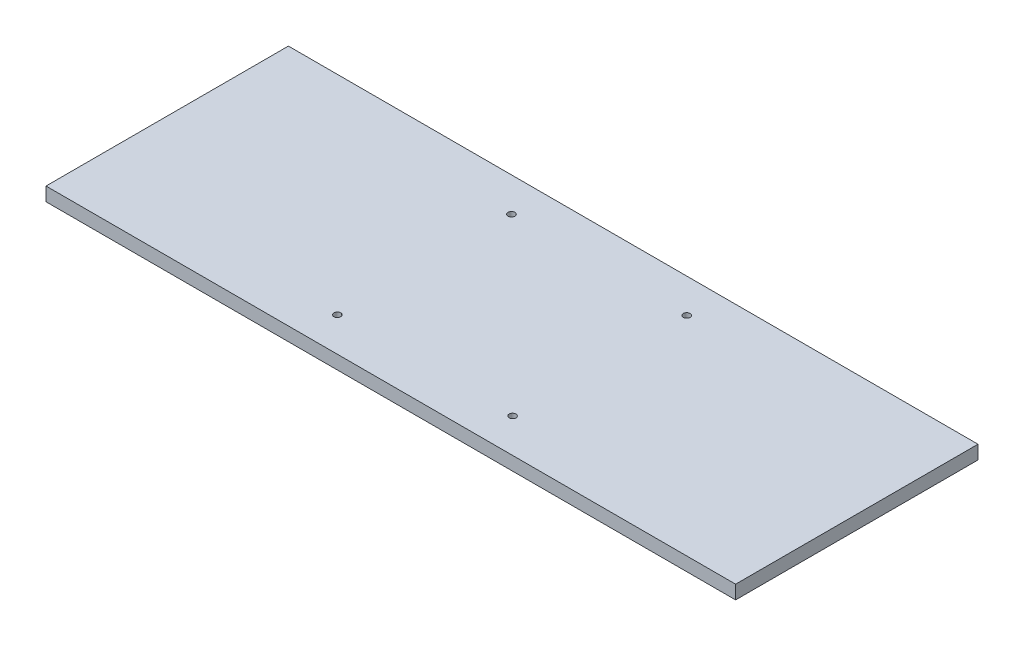
SolidWorks part; units mm, degrees
ref_plane "Front Plane" through (0, 0, 0) normal (0, 0, 1) x (1, 0, 0)
ref_plane "Top Plane" through (0, 0, 0) normal (0, 1, 0) x (1, 0, 0)
ref_plane "Right Plane" through (0, 0, 0) normal (1, 0, 0) x (0, 0, -1)
sketch "Sketch1" plane through (0, 0, 0) normal (0, 1, 0) x (1, 0, 0)
  line L1 (0, 0) -> (404, 0)
  line L2 (0, 0) -> (0, 142)
  line L3 (0, 142) -> (404, 142)
  line L4 (404, 0) -> (404, 142)
  circle A0 centre (150.6667, 20) radius 2 construction
  circle A1 centre (253.3333, 20) radius 2 construction
  circle A2 centre (253.3333, 122) radius 2 construction
  circle A3 centre (150.6667, 122) radius 2 construction
  circle A4 centre (150.6667, 20) radius 2
  circle A5 centre (253.3333, 20) radius 2
  circle A6 centre (253.3333, 122) radius 2
  circle A7 centre (150.6667, 122) radius 2
  dimension "D1" = 142
  dimension "D2" = 404
extrude "Boss-Extrude1" add sketch "Sketch1" along normal blind 8
